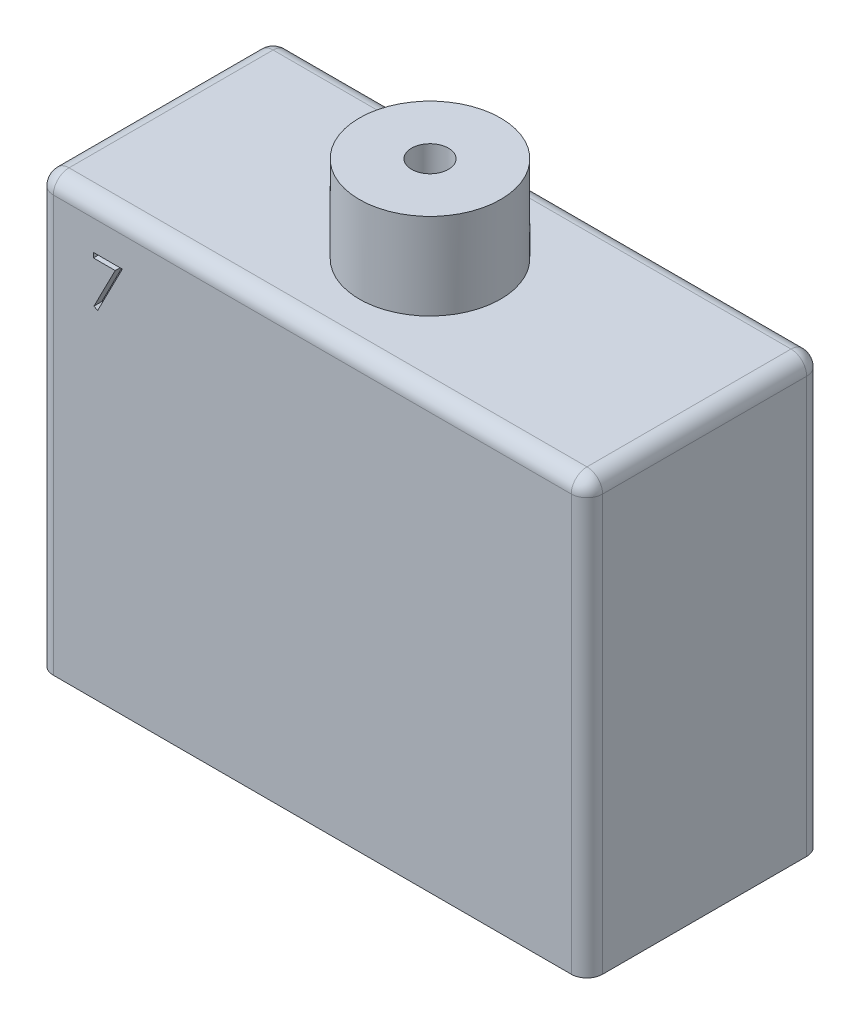
SolidWorks part; units mm, degrees
ref_plane "Alzado" through (0, 0, 0) normal (0, 0, 1) x (1, 0, 0)
ref_plane "Planta" through (0, 0, 0) normal (0, 1, 0) x (1, 0, 0)
ref_plane "Vista lateral" through (0, 0, 0) normal (1, 0, 0) x (0, 0, -1)
sketch "Croquis1" plane through (0, 0, 0) normal (0, 1, 0) x (1, 0, 0)
  line L1 (-35, -15) -> (35, -15)
  line L2 (-35, -15) -> (-35, 15)
  line L3 (-35, 15) -> (35, 15)
  line L4 (35, -15) -> (35, 15)
  line L5 (-35, -15) -> (35, 15) construction
  line L6 (-35, 15) -> (35, -15) construction
  point P0 (0, 0)
extrude "Saliente-Extruir1" add sketch "Croquis1" along normal blind 55
sketch "Croquis9" plane through (0, 0, -15) normal (0, 0, -1) x (-1, 0, 0)
  line L0 (0, 0) -> (0, 32) construction
  line L1 (-35, 0) -> (35, 0) construction
  line L2 (0, 32) -> (-27.5, 32) construction
  line L3 (0, 32) -> (27.5, 32) construction
  circle A0 centre (-27.5, 32) radius 4.15
  circle A1 centre (27.5, 32) radius 4.15
extrude "Cortar-Extruir6" cut sketch "Croquis9" against normal blind 27
fillet "Redondeo1" radius 2 8 edges at (-35, 27.5, 15) (35, 27.5, 15) (35, 27.5, -15) (-35, 27.5, -15) (0, 55, -15) (-35, 55, 0) (0, 55, 15) (35, 55, 0)
sketch "Croquis12" plane through (0, 0, 15) normal (0, 0, 1) x (1, 0, 0)
  line L0 (-33, 43.2214) -> (-19.4094, 43.2214) construction
  line L1 (-33, 53) -> (-33, 0) construction
  text T0 "7" font "Century Gothic" height 6
extrude "Cortar-Extruir9" cut sketch "Croquis12" against normal blind 1
sketch "Croquis13" plane through (0, 55, 0) normal (0, 1, 0) x (1, 0, 0)
  circle A0 centre (0, 0) radius 9
extrude "Saliente-Extruir2" add sketch "Croquis13" along normal blind 11
sketch "Croquis14" plane through (0, 66, 0) normal (0, 1, 0) x (1, 0, 0)
  circle A0 centre (0, 0) radius 2.35
extrude "Cortar-Extruir10" cut sketch "Croquis14" against normal blind 44
